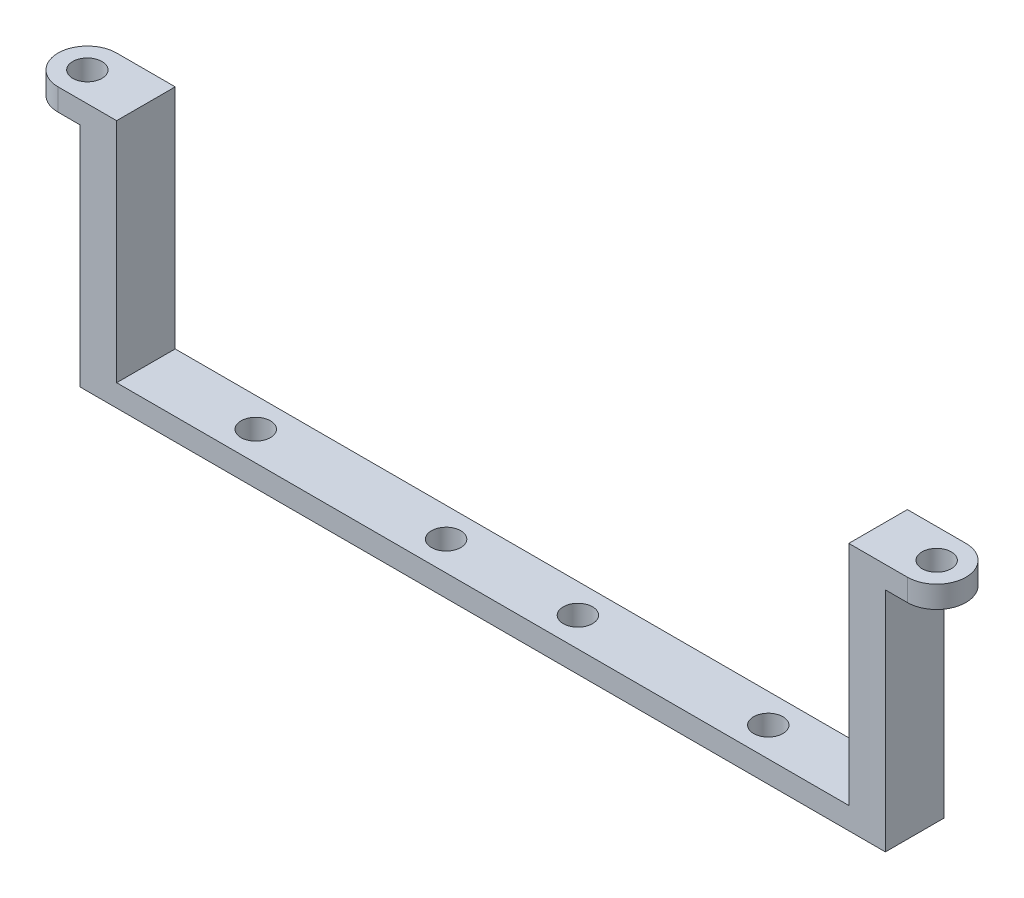
SolidWorks part; units mm, degrees
ref_plane "Front Plane" through (0, 0, 0) normal (0, 0, 1) x (1, 0, 0)
ref_plane "Top Plane" through (0, 0, 0) normal (0, 1, 0) x (1, 0, 0)
ref_plane "Right Plane" through (0, 0, 0) normal (1, 0, 0) x (0, 0, -1)
sketch "Sketch1" plane through (0, 0, 0) normal (0, 1, 0) x (1, 0, 0)
  line L0 (0, 0) -> (0, 4) construction
  line L1 (55, 4) -> (-55, 4)
  line L2 (55, 4) -> (55, -4)
  line L3 (55, -4) -> (-55, -4)
  line L4 (-55, 4) -> (-55, -4)
  line L5 (55, 4) -> (-55, -4) construction
  line L6 (55, -4) -> (-55, 4) construction
  circle A0 centre (-35, 0) radius 2
  circle A1 centre (35, 0) radius 2
  circle A2 centre (-9, 0) radius 2
  circle A3 centre (9, 0) radius 2
  point P0 (0, 0)
  point P14 (0, 0)
  dimension "D3" = 35
  dimension "D7" = 9
  dimension "D1" = 8
  dimension "D2" = 110
  dimension "D4" = 35
  dimension "D5" = 4
  dimension "D6" = 4
  dimension "D8" = 9
  dimension "D9" = 4
  dimension "D10" = 4
extrude "Boss-Extrude1" add sketch "Sketch1" along normal blind 3
sketch "Sketch2" plane through (0, 3, 0) normal (0, 1, 0) x (1, 0, 0)
  line L0 (-55, -4) -> (55, -4) construction
  line L1 (-55, 4) -> (-50, 4)
  line L2 (-55, 4) -> (-55, -4)
  line L3 (-55, -4) -> (-50, -4)
  line L4 (-50, 4) -> (-50, -4)
  line L5 (55, 4) -> (-55, 4) construction
  line L6 (50, 4) -> (55, 4)
  line L7 (50, 4) -> (50, -4)
  line L8 (50, -4) -> (55, -4)
  line L9 (55, 4) -> (55, -4)
  dimension "D1" = 5
  dimension "D2" = 5
extrude "Boss-Extrude2" add sketch "Sketch2" along normal blind 28
sketch "Sketch3" plane through (0, 31, 0) normal (0, 1, 0) x (1, 0, 0)
  line L0 (0, 0) -> (0, 4) construction
  line L1 (-50, 4) -> (-58, 4)
  line L5 (50, 4) -> (-50, 4) construction
  line L9 (-50, 4) -> (-50, -4)
  line L10 (-50, -4) -> (-58, -4)
  line L11 (-58, 4) -> (-58, -4) construction
  line L12 (50, 4) -> (58, 4)
  line L13 (50, 4) -> (50, -4)
  line L14 (50, -4) -> (58, -4)
  arc A4 (-58, 4) -> (-58, -4) centre (-58, 0) ccw
  circle A5 centre (-58, 0) radius 2
  circle A6 centre (58, 0) radius 2
  arc A7 (58, 4) -> (58, -4) centre (58, 0) cw
  dimension "D2" = 8
extrude "Boss-Extrude3" add sketch "Sketch3" along normal blind 3
